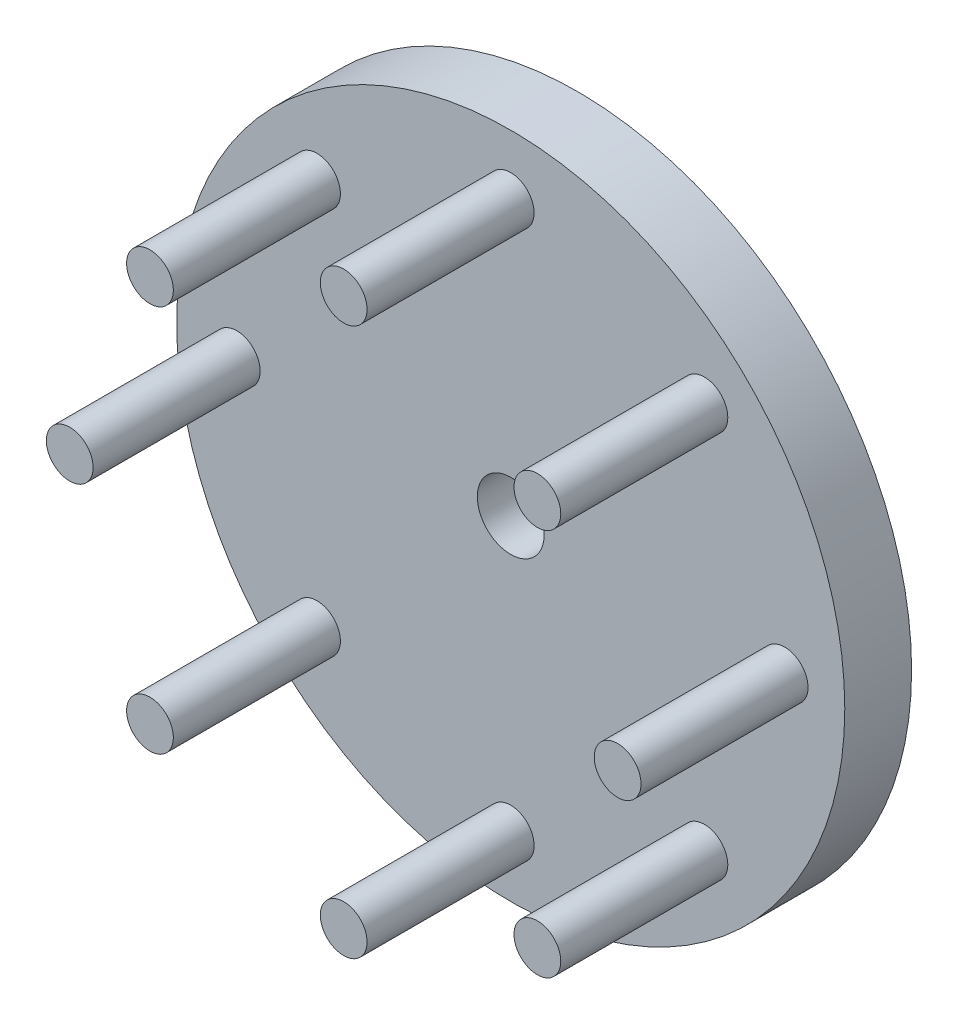
SolidWorks part; units mm, degrees
ref_plane "Front Plane" through (0, 0, 0) normal (0, 0, 1) x (1, 0, 0)
ref_plane "Top Plane" through (0, 0, 0) normal (0, 1, 0) x (1, 0, 0)
ref_plane "Right Plane" through (0, 0, 0) normal (1, 0, 0) x (0, 0, -1)
sketch "Sketch1" plane through (0, 0, 0) normal (0, 0, 1) x (1, 0, 0)
  circle A0 centre (0, 0) radius 50
  circle A1 centre (0, 0) radius 5
  circle A2 centre (0, 0) radius 40 construction
  dimension "D1" = 100
  dimension "D2" = 80
  dimension "D3" = 10
extrude "Boss-Extrude1" add sketch "Sketch1" along normal blind 10
sketch "Sketch2" plane through (0, 0, 10) normal (0, 0, 1) x (1, 0, 0)
  circle A0 centre (0, 0) radius 41
  circle A1 centre (0, 41) radius 3.5
  circle A2 centre (28.9914, 28.9914) radius 3.5
  circle A3 centre (41, 0) radius 3.5
  circle A4 centre (28.9914, -28.9914) radius 3.5
  circle A5 centre (0, -41) radius 3.5
  circle A6 centre (-28.9914, -28.9914) radius 3.5
  circle A7 centre (-41, 0) radius 3.5
  circle A8 centre (-28.9914, 28.9914) radius 3.5
  point P22 (0, 0)
  dimension "D1" = 82
  dimension "D2" = 7
  dimension "D3" = 8
extrude "Boss-Extrude2" add sketch "Sketch2" along normal blind 25 contours A1 | A2 | A3 | A4 | A5 | A6 | A7 | A8
